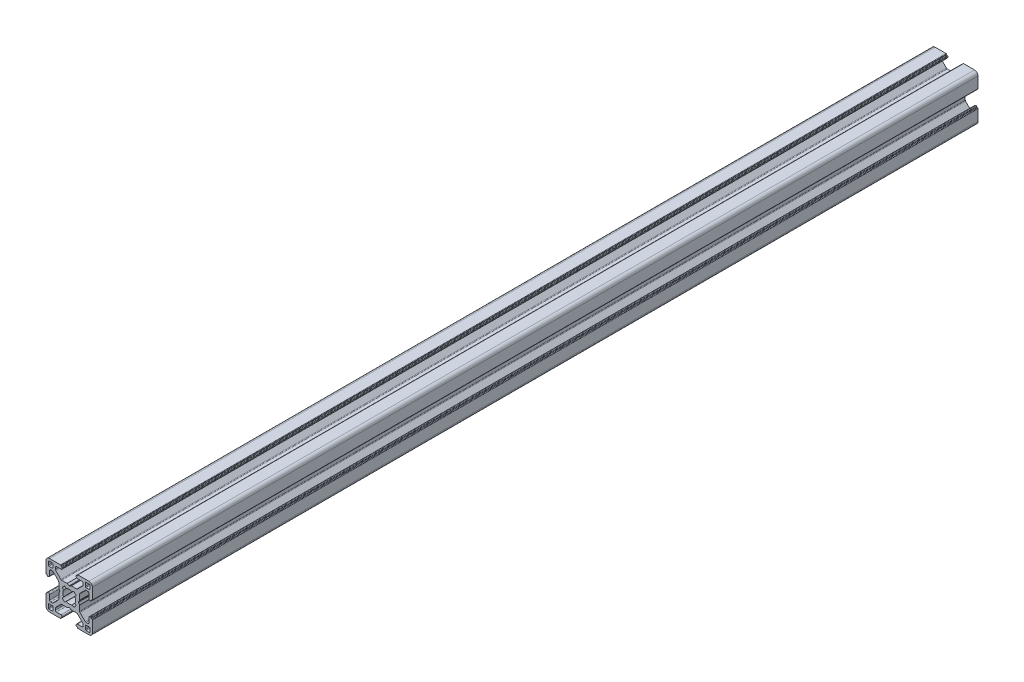
SolidWorks part; units mm, degrees
material "6063-O, Barra estrusa (SS)"
ref_plane "Piano frontale" through (0, 0, 0) normal (0, 0, 1) x (1, 0, 0)
ref_plane "Piano superiore" through (0, 0, 0) normal (0, 1, 0) x (1, 0, 0)
ref_plane "Piano destro" through (0, 0, 0) normal (1, 0, 0) x (0, 0, -1)
ref_plane "Piano1" through (0, 0, 100) normal (0, 0, 1) x (1, 0, 0)
sketch "Schizzo1" plane through (0, 0, 100) normal (0, 0, 1) x (1, 0, 0)
  line L0 (-1.9139, 2.9896) -> (-1.2582, 2.4453)
  line L1 (1.2582, 2.4453) -> (1.9139, 2.9896)
  line L2 (2.9922, 1.9099) -> (2.4453, 1.2582)
  line L3 (2.4453, -1.2582) -> (2.9922, -1.9099)
  line L4 (1.9139, -2.9896) -> (1.2582, -2.4453)
  line L5 (-1.2582, -2.4453) -> (-1.9139, -2.9896)
  line L6 (-2.9922, -1.9099) -> (-2.4453, -1.2582)
  line L7 (-2.4453, 1.2582) -> (-2.9922, 1.9099)
  line L8 (-9.3, 3) -> (-9, 3)
  line L9 (-8.5, 3.5) -> (-8.5, 5.5)
  line L10 (-8, 6) -> (-7.2678, 6)
  line L11 (-6.9142, 5.8536) -> (-4.6464, 3.5858)
  line L12 (-4.5, 3.2322) -> (-4.5, 0.9536)
  line L13 (-4.4732, 0.8536) -> (-4.0381, 0.1)
  line L14 (-4.0381, -0.1) -> (-4.4732, -0.8536)
  line L15 (-4.5, -0.9536) -> (-4.5, -3.2322)
  line L16 (-4.6464, -3.5858) -> (-6.9142, -5.8536)
  line L17 (-7.2678, -6) -> (-8, -6)
  line L18 (-8.5, -5.5) -> (-8.5, -3.5)
  line L19 (-9, -3) -> (-9.3, -3)
  line L20 (-9.5, -3.2) -> (-9.5, -3.35)
  line L21 (-9.7, -3.55) -> (-9.8, -3.55)
  line L22 (-10, -3.75) -> (-10, -8.5)
  line L23 (-8.5, -10) -> (-3.75, -10)
  line L24 (-3.55, -9.8) -> (-3.55, -9.7)
  line L25 (-3.35, -9.5) -> (-3.2, -9.5)
  line L26 (-3, -9.3) -> (-3, -9)
  line L27 (-3.5, -8.5) -> (-5.5, -8.5)
  line L28 (-6, -8) -> (-6, -7.2678)
  line L29 (-5.8536, -6.9142) -> (-3.5858, -4.6464)
  line L30 (-3.2322, -4.5) -> (-0.9536, -4.5)
  line L31 (-0.8536, -4.4732) -> (-0.1, -4.0381)
  line L32 (0.1, -4.0381) -> (0.8536, -4.4732)
  line L33 (0.9536, -4.5) -> (3.2322, -4.5)
  line L34 (3.5858, -4.6464) -> (5.8536, -6.9142)
  line L35 (6, -7.2678) -> (6, -8)
  line L36 (5.5, -8.5) -> (3.5, -8.5)
  line L37 (3, -9) -> (3, -9.3)
  line L38 (3.2, -9.5) -> (3.35, -9.5)
  line L39 (3.55, -9.7) -> (3.55, -9.8)
  line L40 (3.75, -10) -> (8.5, -10)
  line L41 (10, -8.5) -> (10, -3.75)
  line L42 (9.8, -3.55) -> (9.7, -3.55)
  line L43 (9.5, -3.35) -> (9.5, -3.2)
  line L44 (9.3, -3) -> (9, -3)
  line L45 (8.5, -3.5) -> (8.5, -5.5)
  line L46 (8, -6) -> (7.2678, -6)
  line L47 (6.9142, -5.8536) -> (4.6464, -3.5858)
  line L48 (4.5, -3.2322) -> (4.5, -0.9536)
  line L49 (4.4732, -0.8536) -> (4.0381, -0.1)
  line L50 (4.0381, 0.1) -> (4.4732, 0.8536)
  line L51 (4.5, 0.9536) -> (4.5, 3.2322)
  line L52 (4.6464, 3.5858) -> (6.9142, 5.8536)
  line L53 (7.2678, 6) -> (8, 6)
  line L54 (8.5, 5.5) -> (8.5, 3.5)
  line L55 (9, 3) -> (9.3, 3)
  line L56 (9.5, 3.2) -> (9.5, 3.35)
  line L57 (9.7, 3.55) -> (9.8, 3.55)
  line L58 (10, 3.75) -> (10, 8.5)
  line L59 (8.5, 10) -> (3.75, 10)
  line L60 (3.55, 9.8) -> (3.55, 9.7)
  line L61 (3.35, 9.5) -> (3.2, 9.5)
  line L62 (3, 9.3) -> (3, 9)
  line L63 (3.5, 8.5) -> (5.5, 8.5)
  line L64 (6, 8) -> (6, 7.2678)
  line L65 (5.8536, 6.9142) -> (3.5858, 4.6464)
  line L66 (3.2322, 4.5) -> (0.9536, 4.5)
  line L67 (0.8536, 4.4732) -> (0.1, 4.0381)
  line L68 (-0.1, 4.0381) -> (-0.8536, 4.4732)
  line L69 (-0.9536, 4.5) -> (-3.2322, 4.5)
  line L70 (-3.5858, 4.6464) -> (-5.8536, 6.9142)
  line L71 (-6, 7.2678) -> (-6, 8)
  line L72 (-5.5, 8.5) -> (-3.5, 8.5)
  line L73 (-3, 9) -> (-3, 9.3)
  line L74 (-3.2, 9.5) -> (-3.35, 9.5)
  line L75 (-3.55, 9.7) -> (-3.55, 9.8)
  line L76 (-3.75, 10) -> (-8.5, 10)
  line L77 (-10, 8.5) -> (-10, 3.75)
  line L78 (-9.8, 3.55) -> (-9.7, 3.55)
  line L79 (-9.5, 3.35) -> (-9.5, 3.2)
  line L80 (8.7, 7) -> (7.3, 7)
  line L81 (-7.3, 7) -> (-8.7, 7)
  line L82 (-7, 7.3) -> (-7, 8.7)
  line L83 (-7.3, 9) -> (-8.7, 9)
  line L84 (-9, 7.3) -> (-9, 8.7)
  line L85 (9, 7.3) -> (9, 8.7)
  line L86 (8.7, 9) -> (7.3, 9)
  line L87 (7, 7.3) -> (7, 8.7)
  line L88 (8.7, -9) -> (7.3, -9)
  line L89 (9, -8.7) -> (9, -7.3)
  line L90 (8.7, -7) -> (7.3, -7)
  line L91 (7, -8.7) -> (7, -7.3)
  line L92 (-7.3, -9) -> (-8.7, -9)
  line L93 (-7, -8.7) -> (-7, -7.3)
  line L94 (-7.3, -7) -> (-8.7, -7)
  line L95 (-9, -8.7) -> (-9, -7.3)
  arc A0 (-1.2582, 2.4453) -> (1.2582, 2.4453) centre (0, 0) cw
  arc A1 (1.9139, 2.9896) -> (2.9922, 1.9099) centre (0, 0) cw
  arc A2 (2.4453, 1.2582) -> (2.4453, -1.2582) centre (0, 0) cw
  arc A3 (2.9922, -1.9099) -> (1.9139, -2.9896) centre (0, 0) cw
  arc A4 (1.2582, -2.4453) -> (-1.2582, -2.4453) centre (0, 0) cw
  arc A5 (-1.9139, -2.9896) -> (-2.9922, -1.9099) centre (0, 0) cw
  arc A6 (-2.4453, -1.2582) -> (-2.4453, 1.2582) centre (0, 0) cw
  arc A7 (-2.9922, 1.9099) -> (-1.9139, 2.9896) centre (0, 0) cw
  arc A8 (-9.5, 3.2) -> (-9.3, 3) centre (-9.3, 3.2) ccw
  arc A9 (-9, 3) -> (-8.5, 3.5) centre (-9, 3.5) ccw
  arc A10 (-8.5, 5.5) -> (-8, 6) centre (-8, 5.5) cw
  arc A11 (-7.2678, 6) -> (-6.9142, 5.8536) centre (-7.2678, 5.5) cw
  arc A12 (-4.6464, 3.5858) -> (-4.5, 3.2322) centre (-5, 3.2322) cw
  arc A13 (-4.5, 0.9536) -> (-4.4732, 0.8536) centre (-4.3, 0.9536) ccw
  arc A14 (-4.0381, 0.1) -> (-4.0381, -0.1) centre (-4.2113, 0) cw
  arc A15 (-4.4732, -0.8536) -> (-4.5, -0.9536) centre (-4.3, -0.9536) ccw
  arc A16 (-4.5, -3.2322) -> (-4.6464, -3.5858) centre (-5, -3.2322) cw
  arc A17 (-6.9142, -5.8536) -> (-7.2678, -6) centre (-7.2678, -5.5) cw
  arc A18 (-8, -6) -> (-8.5, -5.5) centre (-8, -5.5) cw
  arc A19 (-8.5, -3.5) -> (-9, -3) centre (-9, -3.5) ccw
  arc A20 (-9.3, -3) -> (-9.5, -3.2) centre (-9.3, -3.2) ccw
  arc A21 (-9.5, -3.35) -> (-9.7, -3.55) centre (-9.7, -3.35) cw
  arc A22 (-9.8, -3.55) -> (-10, -3.75) centre (-9.8, -3.75) ccw
  arc A23 (-10, -8.5) -> (-8.5, -10) centre (-8.5, -8.5) ccw
  arc A24 (-3.75, -10) -> (-3.55, -9.8) centre (-3.75, -9.8) ccw
  arc A25 (-3.55, -9.7) -> (-3.35, -9.5) centre (-3.35, -9.7) cw
  arc A26 (-3.2, -9.5) -> (-3, -9.3) centre (-3.2, -9.3) ccw
  arc A27 (-3, -9) -> (-3.5, -8.5) centre (-3.5, -9) ccw
  arc A28 (-5.5, -8.5) -> (-6, -8) centre (-5.5, -8) cw
  arc A29 (-6, -7.2678) -> (-5.8536, -6.9142) centre (-5.5, -7.2678) cw
  arc A30 (-3.5858, -4.6464) -> (-3.2322, -4.5) centre (-3.2322, -5) cw
  arc A31 (-0.9536, -4.5) -> (-0.8536, -4.4732) centre (-0.9536, -4.3) ccw
  arc A32 (-0.1, -4.0381) -> (0.1, -4.0381) centre (0, -4.2113) cw
  arc A33 (0.8536, -4.4732) -> (0.9536, -4.5) centre (0.9536, -4.3) ccw
  arc A34 (3.2322, -4.5) -> (3.5858, -4.6464) centre (3.2322, -5) cw
  arc A35 (5.8536, -6.9142) -> (6, -7.2678) centre (5.5, -7.2678) cw
  arc A36 (6, -8) -> (5.5, -8.5) centre (5.5, -8) cw
  arc A37 (3.5, -8.5) -> (3, -9) centre (3.5, -9) ccw
  arc A38 (3, -9.3) -> (3.2, -9.5) centre (3.2, -9.3) ccw
  arc A39 (3.35, -9.5) -> (3.55, -9.7) centre (3.35, -9.7) cw
  arc A40 (3.55, -9.8) -> (3.75, -10) centre (3.75, -9.8) ccw
  arc A41 (8.5, -10) -> (10, -8.5) centre (8.5, -8.5) ccw
  arc A42 (10, -3.75) -> (9.8, -3.55) centre (9.8, -3.75) ccw
  arc A43 (9.7, -3.55) -> (9.5, -3.35) centre (9.7, -3.35) cw
  arc A44 (9.5, -3.2) -> (9.3, -3) centre (9.3, -3.2) ccw
  arc A45 (9, -3) -> (8.5, -3.5) centre (9, -3.5) ccw
  arc A46 (8.5, -5.5) -> (8, -6) centre (8, -5.5) cw
  arc A47 (7.2678, -6) -> (6.9142, -5.8536) centre (7.2678, -5.5) cw
  arc A48 (4.6464, -3.5858) -> (4.5, -3.2322) centre (5, -3.2322) cw
  arc A49 (4.5, -0.9536) -> (4.4732, -0.8536) centre (4.3, -0.9536) ccw
  arc A50 (4.0381, -0.1) -> (4.0381, 0.1) centre (4.2113, 0) cw
  arc A51 (4.4732, 0.8536) -> (4.5, 0.9536) centre (4.3, 0.9536) ccw
  arc A52 (4.5, 3.2322) -> (4.6464, 3.5858) centre (5, 3.2322) cw
  arc A53 (6.9142, 5.8536) -> (7.2678, 6) centre (7.2678, 5.5) cw
  arc A54 (8, 6) -> (8.5, 5.5) centre (8, 5.5) cw
  arc A55 (8.5, 3.5) -> (9, 3) centre (9, 3.5) ccw
  arc A56 (9.3, 3) -> (9.5, 3.2) centre (9.3, 3.2) ccw
  arc A57 (9.5, 3.35) -> (9.7, 3.55) centre (9.7, 3.35) cw
  arc A58 (9.8, 3.55) -> (10, 3.75) centre (9.8, 3.75) ccw
  arc A59 (10, 8.5) -> (8.5, 10) centre (8.5, 8.5) ccw
  arc A60 (3.75, 10) -> (3.55, 9.8) centre (3.75, 9.8) ccw
  arc A61 (3.55, 9.7) -> (3.35, 9.5) centre (3.35, 9.7) cw
  arc A62 (3.2, 9.5) -> (3, 9.3) centre (3.2, 9.3) ccw
  arc A63 (3, 9) -> (3.5, 8.5) centre (3.5, 9) ccw
  arc A64 (5.5, 8.5) -> (6, 8) centre (5.5, 8) cw
  arc A65 (6, 7.2678) -> (5.8536, 6.9142) centre (5.5, 7.2678) cw
  arc A66 (3.5858, 4.6464) -> (3.2322, 4.5) centre (3.2322, 5) cw
  arc A67 (0.9536, 4.5) -> (0.8536, 4.4732) centre (0.9536, 4.3) ccw
  arc A68 (0.1, 4.0381) -> (-0.1, 4.0381) centre (0, 4.2113) cw
  arc A69 (-0.8536, 4.4732) -> (-0.9536, 4.5) centre (-0.9536, 4.3) ccw
  arc A70 (-3.2322, 4.5) -> (-3.5858, 4.6464) centre (-3.2322, 5) cw
  arc A71 (-5.8536, 6.9142) -> (-6, 7.2678) centre (-5.5, 7.2678) cw
  arc A72 (-6, 8) -> (-5.5, 8.5) centre (-5.5, 8) cw
  arc A73 (-3.5, 8.5) -> (-3, 9) centre (-3.5, 9) ccw
  arc A74 (-3, 9.3) -> (-3.2, 9.5) centre (-3.2, 9.3) ccw
  arc A75 (-3.35, 9.5) -> (-3.55, 9.7) centre (-3.35, 9.7) cw
  arc A76 (-3.55, 9.8) -> (-3.75, 10) centre (-3.75, 9.8) ccw
  arc A77 (-8.5, 10) -> (-10, 8.5) centre (-8.5, 8.5) ccw
  arc A78 (-10, 3.75) -> (-9.8, 3.55) centre (-9.8, 3.75) ccw
  arc A79 (-9.7, 3.55) -> (-9.5, 3.35) centre (-9.7, 3.35) cw
  arc A80 (-8.7, 7) -> (-9, 7.3) centre (-8.7, 7.3) cw
  arc A81 (-7, 8.7) -> (-7.3, 9) centre (-7.3, 8.7) ccw
  arc A82 (-7.3, 7) -> (-7, 7.3) centre (-7.3, 7.3) ccw
  arc A83 (-8.7, 9) -> (-9, 8.7) centre (-8.7, 8.7) ccw
  arc A84 (7.3, 7) -> (7, 7.3) centre (7.3, 7.3) cw
  arc A85 (9, 8.7) -> (8.7, 9) centre (8.7, 8.7) ccw
  arc A86 (8.7, 7) -> (9, 7.3) centre (8.7, 7.3) ccw
  arc A87 (7.3, 9) -> (7, 8.7) centre (7.3, 8.7) ccw
  arc A88 (7.3, -9) -> (7, -8.7) centre (7.3, -8.7) cw
  arc A89 (9, -7.3) -> (8.7, -7) centre (8.7, -7.3) ccw
  arc A90 (8.7, -9) -> (9, -8.7) centre (8.7, -8.7) ccw
  arc A91 (7.3, -7) -> (7, -7.3) centre (7.3, -7.3) ccw
  arc A92 (-8.7, -9) -> (-9, -8.7) centre (-8.7, -8.7) cw
  arc A93 (-7, -7.3) -> (-7.3, -7) centre (-7.3, -7.3) ccw
  arc A94 (-7.3, -9) -> (-7, -8.7) centre (-7.3, -8.7) ccw
  arc A95 (-8.7, -7) -> (-9, -7.3) centre (-8.7, -7.3) ccw
  dimension "D1" = 0.3
  dimension "D2" = 1
  dimension "D3" = 1
  dimension "D4" = 1
  dimension "D7" = 1
  dimension "D8" = 1
  dimension "D9" = 1
  dimension "D10" = 1
  dimension "D5" = 2
  dimension "D6" = 2
extrude "Estrusione-Estrusione1" add sketch "Schizzo1" against normal blind 382
